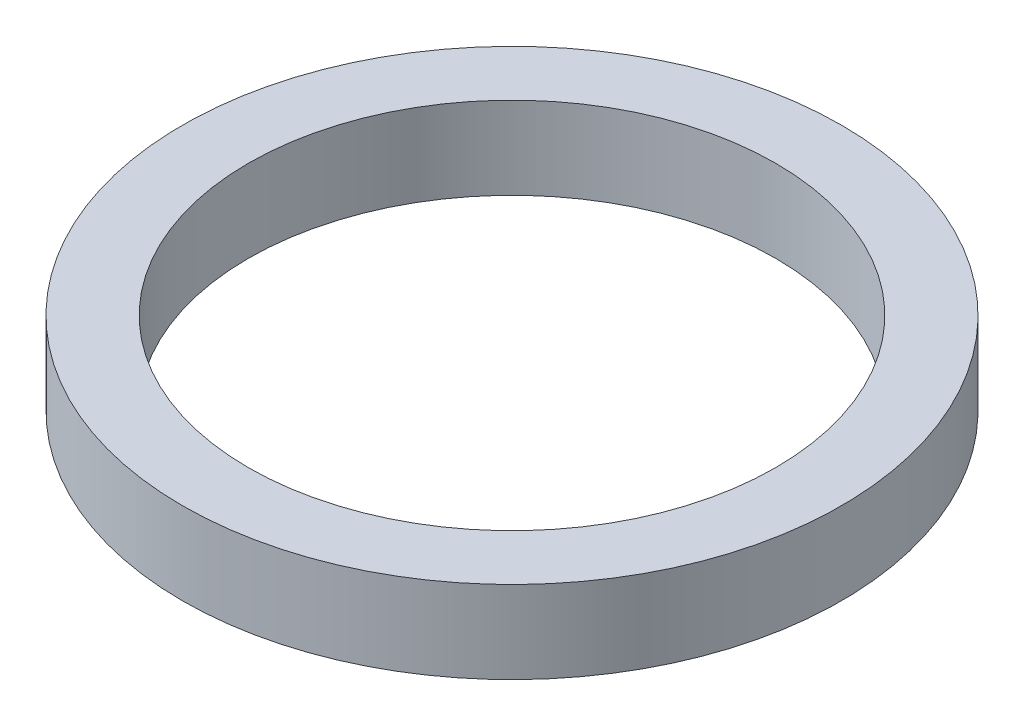
SolidWorks part; units mm, degrees
ref_plane "Front Plane" through (0, 0, 0) normal (0, 0, 1) x (1, 0, 0)
ref_plane "Top Plane" through (0, 0, 0) normal (0, 1, 0) x (1, 0, 0)
ref_plane "Right Plane" through (0, 0, 0) normal (1, 0, 0) x (0, 0, -1)
sketch "Sketch1" plane through (0, 0, 0) normal (0, 1, 0) x (1, 0, 0)
  circle A0 centre (0, 0) radius 1.6
  circle A1 centre (0, 0) radius 2
  point P5 (0.0198, 0)
  dimension "D1" = 4
  dimension "D2" = 3.2
extrude "Boss-Extrude1" add sketch "Sketch1" along normal blind 0.5
equation "\"ID\" = 3.2mm"
equation "\"OD\"= 4mm"
equation "\"t\"= 0.5mm"
equation "\"D1@Boss-Extrude1\"=\"t\""
equation "\"D1@Sketch1\"=\"OD\""
equation "\"D2@Sketch1\"=\"ID\""
